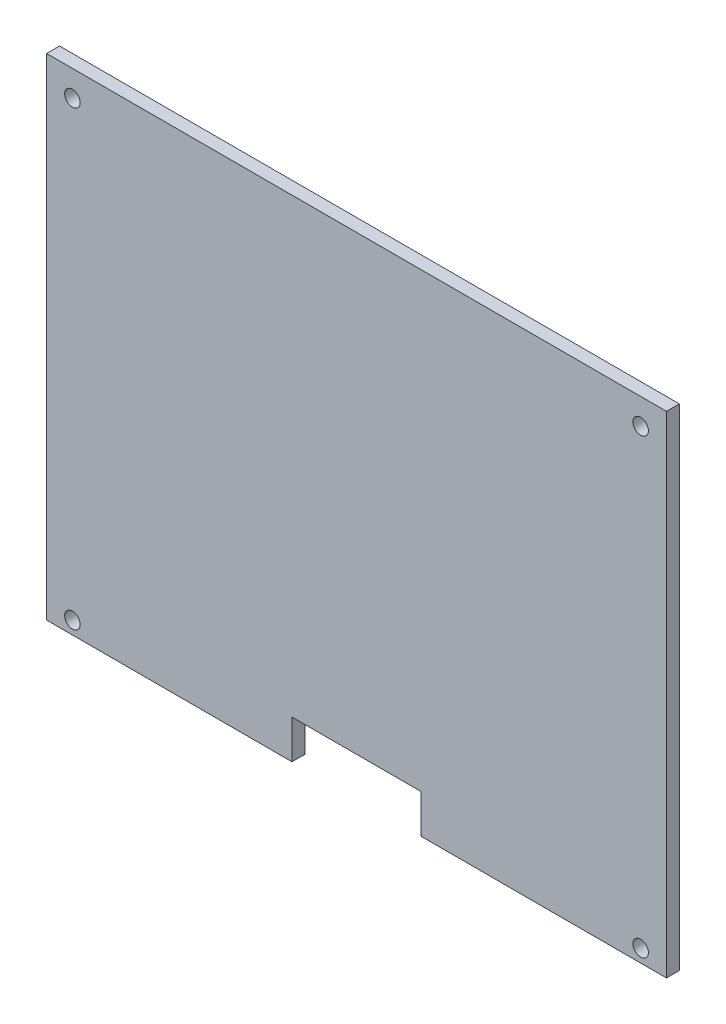
SolidWorks part; units mm, degrees
ref_plane "Plan de face" through (0, 0, 0) normal (0, 0, 1) x (1, 0, 0)
ref_plane "Plan de dessus" through (0, 0, 0) normal (0, 1, 0) x (1, 0, 0)
ref_plane "Plan de droite" through (0, 0, 0) normal (1, 0, 0) x (0, 0, -1)
sketch "Esquisse1" plane through (0, 0, 0) normal (0, 0, 1) x (1, 0, 0)
  line L1 (0, 0) -> (240, 0)
  line L2 (0, 0) -> (0, -190)
  line L3 (0, -190) -> (240, -190)
  line L4 (240, 0) -> (240, -190)
  dimension "D1" = 240
  dimension "D2" = 190
extrude "Boss.-Extru.1" add sketch "Esquisse1" along normal blind 5
sketch "Esquisse2" plane through (0, 0, 5) normal (0, 0, 1) x (1, 0, 0)
  line L0 (95, -190) -> (95, -175)
  line L1 (0, -190) -> (240, -190) construction
  line L2 (95, -175) -> (145, -175)
  line L3 (145, -175) -> (145, -190)
  line L4 (145, -190) -> (95, -190)
  line L5 (0, 0) -> (0, -190) construction
  dimension "D1" = 50
  dimension "D2" = 15
  dimension "D3" = 95
extrude "Enlèv. mat.-Extru.1" cut sketch "Esquisse2" against normal blind 5 contours L4 L0 L2 L3
sketch "Esquisse3" plane through (0, 0, 5) normal (0, 0, 1) x (1, 0, 0)
  line L0 (120, 0) -> (120, -175) construction
  line L1 (240, 0) -> (0, 0) construction
  line L2 (95, -175) -> (145, -175) construction
  line L3 (0, 0) -> (0, -190) construction
  line L4 (0, -190) -> (95, -190) construction
  circle A0 centre (10, -10) radius 3
  circle A1 centre (10, -185) radius 3
  circle A2 centre (230, -185) radius 3
  circle A3 centre (230, -10) radius 3
  dimension "D1" = 6
  dimension "D6" = 6
  dimension "D2" = 10
  dimension "D3" = 10
  dimension "D4" = 5
  dimension "D5" = 10
extrude "Enlèv. mat.-Extru.2" cut sketch "Esquisse3" against normal blind 10
